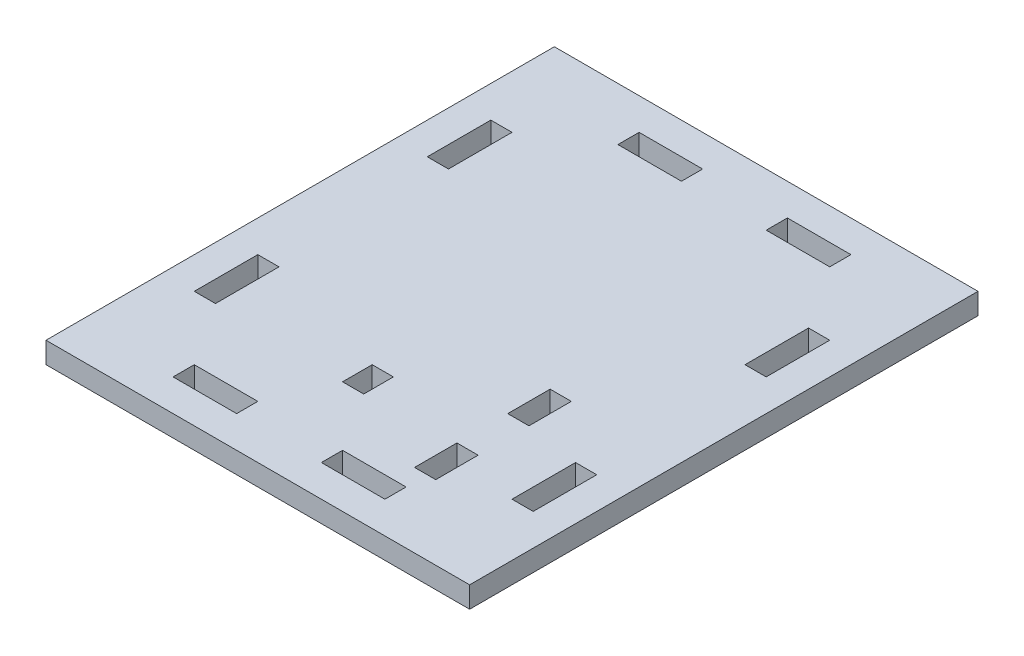
SolidWorks part; units mm, degrees
ref_plane "Front" through (0, 0, 0) normal (0, 0, 1) x (1, 0, 0)
ref_plane "Top" through (0, 0, 0) normal (0, 1, 0) x (1, 0, 0)
ref_plane "Right" through (0, 0, 0) normal (1, 0, 0) x (0, 0, -1)
sketch "Sketch1" plane through (0, 0, 0) normal (0, 1, 0) x (1, 0, 0)
  line L0 (-53.975, 28.575) -> (-53.975, -22.225) construction
  line L1 (63.5, -76.2) -> (-63.5, -76.2)
  line L2 (63.5, -76.2) -> (63.5, 76.2)
  line L3 (63.5, 76.2) -> (-63.5, 76.2)
  line L4 (-63.5, -76.2) -> (-63.5, 76.2)
  line L5 (63.5, -76.2) -> (-63.5, 76.2) construction
  line L6 (63.5, 76.2) -> (-63.5, -76.2) construction
  line L7 (-15.875, -66.675) -> (9.525, -66.675) construction
  line L8 (53.975, -28.575) -> (53.975, 22.225) construction
  line L9 (-28.575, 66.675) -> (-9.525, 66.675)
  line L10 (-28.575, 66.675) -> (-28.575, 60.325)
  line L11 (-28.575, 60.325) -> (-9.525, 60.325)
  line L12 (-9.525, 66.675) -> (-9.525, 60.325)
  line L13 (15.875, 66.675) -> (34.925, 66.675)
  line L14 (15.875, 66.675) -> (15.875, 60.325)
  line L15 (15.875, 60.325) -> (34.925, 60.325)
  line L16 (34.925, 66.675) -> (34.925, 60.325)
  line L17 (-53.975, 47.625) -> (-47.625, 47.625)
  line L18 (-53.975, 47.625) -> (-53.975, 28.575)
  line L19 (-53.975, 28.575) -> (-47.625, 28.575)
  line L20 (-47.625, 47.625) -> (-47.625, 28.575)
  line L21 (-53.975, -22.225) -> (-47.625, -22.225)
  line L22 (-53.975, -22.225) -> (-53.975, -41.275)
  line L23 (-53.975, -41.275) -> (-47.625, -41.275)
  line L24 (-47.625, -22.225) -> (-47.625, -41.275)
  line L25 (-34.925, -60.325) -> (-15.875, -60.325)
  line L26 (-34.925, -60.325) -> (-34.925, -66.675)
  line L27 (-34.925, -66.675) -> (-15.875, -66.675)
  line L28 (-15.875, -60.325) -> (-15.875, -66.675)
  line L29 (9.525, -60.325) -> (28.575, -60.325)
  line L30 (9.525, -60.325) -> (9.525, -66.675)
  line L31 (9.525, -66.675) -> (28.575, -66.675)
  line L32 (28.575, -60.325) -> (28.575, -66.675)
  line L33 (53.975, -47.625) -> (47.625, -47.625)
  line L34 (53.975, -47.625) -> (53.975, -28.575)
  line L35 (53.975, -28.575) -> (47.625, -28.575)
  line L36 (47.625, -47.625) -> (47.625, -28.575)
  line L37 (53.975, 22.225) -> (47.625, 22.225)
  line L38 (53.975, 22.225) -> (53.975, 41.275)
  line L39 (53.975, 41.275) -> (47.625, 41.275)
  line L40 (47.625, 22.225) -> (47.625, 41.275)
  line L41 (15.875, 66.675) -> (-9.525, 66.675) construction
  point P6 (19.1393, -66.675)
  point P7 (20.1712, 66.675)
  dimension "D1" = 19.05
  dimension "D2" = 6.35
  dimension "D3" = 50.8
  dimension "D4" = 19.05
  dimension "D5" = 12.7
  dimension "D6" = 133.35
  dimension "D7" = 107.95
  dimension "D8" = 127
  dimension "D9" = 152.4
  dimension "D10" = 19.05
  dimension "D11" = 9.525
  dimension "D12" = 9.525
  dimension "D13" = 12.7
  dimension "D14" = 25.4
extrude "BASE" add sketch "Sketch1" along normal blind 6.35
sketch "Sketch2" plane through (0, 6.35, 0) normal (0, 1, 0) x (1, 0, 0)
  line L0 (47.625, -47.625) -> (47.625, -28.575) construction
  line L1 (24.765, -13.335) -> (31.115, -13.335)
  line L2 (24.765, -13.335) -> (24.765, -26.035)
  line L3 (24.765, -26.035) -> (31.115, -26.035)
  line L4 (31.115, -13.335) -> (31.115, -26.035)
  line L5 (24.765, -41.275) -> (31.115, -41.275)
  line L6 (24.765, -41.275) -> (24.765, -53.975)
  line L7 (24.765, -53.975) -> (31.115, -53.975)
  line L8 (31.115, -41.275) -> (31.115, -53.975)
  line L9 (9.525, -60.325) -> (28.575, -60.325) construction
  line L11 (-8.255, -33.655) -> (-1.905, -33.655)
  line L12 (-8.255, -33.655) -> (-8.255, -42.545)
  line L13 (-8.255, -42.545) -> (-1.905, -42.545)
  line L14 (-1.905, -33.655) -> (-1.905, -42.545)
  dimension "D1" = 16.51
  dimension "D2" = 6.35
  dimension "D3" = 12.7
  dimension "D4" = 15.24
  dimension "D5" = 6.35
  dimension "D6" = 26.67
  dimension "D7" = 6.35
  dimension "D8" = 8.89
  dimension "D9" = 11.43
extrude "MOTORMOUNTS" cut sketch "Sketch2" against normal through all
